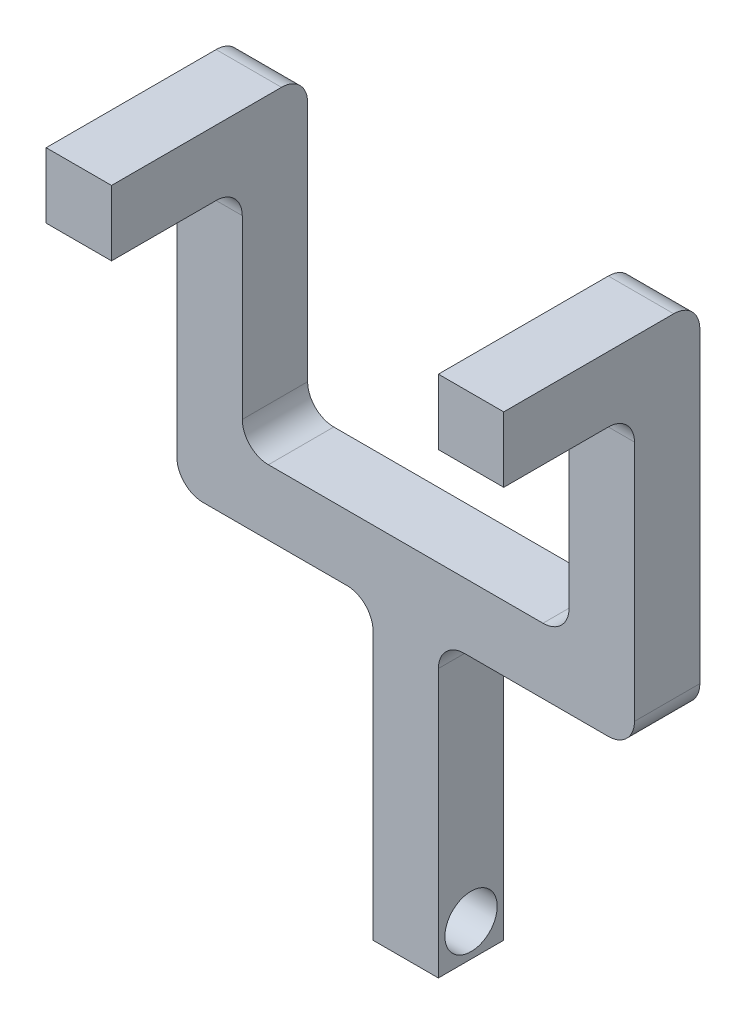
SolidWorks part; units mm, degrees
ref_plane "Plan de face" through (0, 0, 0) normal (0, 0, 1) x (1, 0, 0)
ref_plane "Plan de dessus" through (0, 0, 0) normal (0, 1, 0) x (1, 0, 0)
ref_plane "Plan de droite" through (0, 0, 0) normal (1, 0, 0) x (0, 0, -1)
sketch "Esquisse1" plane through (0, 0, 0) normal (0, 0, 1) x (1, 0, 0)
  line L0 (30, 0) -> (30, 45)
  line L1 (0, 0) -> (70, 0) construction
  line L2 (0, 0) -> (0, 100) construction
  line L3 (0, 100) -> (70, 100) construction
  line L4 (70, 0) -> (70, 100) construction
  line L5 (30, 45) -> (0, 45)
  line L6 (0, 45) -> (0, 100)
  line L7 (0, 100) -> (10, 100)
  line L8 (10, 100) -> (10, 55)
  line L9 (10, 55) -> (60, 55)
  line L10 (60, 55) -> (60, 100)
  line L11 (60, 100) -> (70, 100)
  line L12 (70, 100) -> (70, 45)
  line L13 (70, 45) -> (40, 45)
  line L14 (40, 45) -> (40, 0)
  line L15 (40, 0) -> (30, 0)
  dimension "D1" = 70
  dimension "D2" = 100
  dimension "D3" = 10
  dimension "D4" = 10
  dimension "D5" = 10
  dimension "D6" = 10
extrude "Boss.-Extru.1" add sketch "Esquisse1" along normal blind 10
sketch "Esquisse2" plane through (0, 0, 10) normal (0, 0, 1) x (1, 0, 0)
  line L0 (10, 55) -> (10, 100) construction
  line L1 (0, 100) -> (0, 45) construction
  line L2 (10, 100) -> (0, 100) construction
  line L3 (10, 90) -> (10, 100)
  line L4 (0, 100) -> (0, 90)
  line L5 (10, 100) -> (0, 100)
  line L6 (0, 90) -> (10, 90)
  line L7 (70, 45) -> (70, 100) construction
  line L8 (60, 100) -> (60, 55) construction
  line L9 (70, 100) -> (60, 100) construction
  line L10 (70, 90) -> (70, 100)
  line L11 (60, 100) -> (60, 90)
  line L12 (70, 100) -> (60, 100)
  line L13 (60, 90) -> (70, 90)
  dimension "D1" = 10
  dimension "D2" = 10
extrude "Boss.-Extru.2" add sketch "Esquisse2" along normal blind 20
sketch "Esquisse3" plane through (30, 0, 0) normal (-1, 0, 0) x (0, 0, 1)
  line L2 (10, 0) -> (0, 0) construction
  line L3 (0, 45) -> (0, 0) construction
  circle A0 centre (5, 5) radius 2.5
  dimension "D1" = 5
  dimension "D2" = 5
  dimension "D3" = 5
hole_wizard "Diamètre du perçage Ø8.0 (8)1" positions "Esquisse4" profile "Esquisse6" hole size "Ø8.0" standard "ISO"
sketch "Esquisse4" plane through (30, 0, 0) normal (-1, 0, 0) x (0, 0, 1)
  point P0 (5, 5)
sketch "Esquisse6" plane through (30, 5, 5) normal (0, 1, 0) x (0, 0, 1)
  line L0 (0, 0) -> (0, 12.4034)
  line L1 (0, 12.4034) -> (4, 10)
  line L2 (4, 10) -> (4, 0)
  line L5 (4, 0) -> (0, 0)
  line L10 (0, 12.4034) -> (-4, 10) construction
  line L11 (0, -6.35) -> (0, 107.95) construction
  dimension "Diamètre du perçage" = 8
  dimension "Profondeur du perçage" = 10
  dimension "Angle de pointe" = 118
fillet "Congé1" radius 4 10 edges at (70, 45, 5) (40, 45, 5) (65, 100, 0) (60, 55, 5) (10, 55, 5) (5, 100, 0) (0, 45, 5) (30, 45, 5) (65, 90, 10) (5, 90, 10)
equation "\"long_tot\" = 100"
equation "\"espac_sub_arms\" = 50"
equation "\"épaiss_cadre\"= 10"
equation "\"long_protub\"= 20"
equation "\"D1@Esquisse1\"=\"espac_sub_arms\"+\"épaiss_cadre\"*2"
equation "\"D2@Esquisse1\"=\"long_tot\""
equation "\"D3@Esquisse1\"=\"épaiss_cadre\""
equation "\"D4@Esquisse1\"=\"épaiss_cadre\""
equation "\"D5@Esquisse1\"=\"épaiss_cadre\""
equation "\"D6@Esquisse1\"=\"épaiss_cadre\""
equation "\"D1@Boss.-Extru.1\"=\"épaiss_cadre\""
equation "\"rayon_conge\"= 3"
equation "\"D1@Esquisse2\"=\"épaiss_cadre\""
equation "\"D2@Esquisse2\"=\"épaiss_cadre\""
equation "\"D1@Boss.-Extru.2\"=\"long_protub\""
equation "\"diam_axe\"= 5"
equation "\"D1@Esquisse3\"=\"diam_axe\""
equation "\"D2@Esquisse3\"=\"épaiss_cadre\"/2"
equation "\"D3@Esquisse3\"=\"D2@Esquisse3\""
